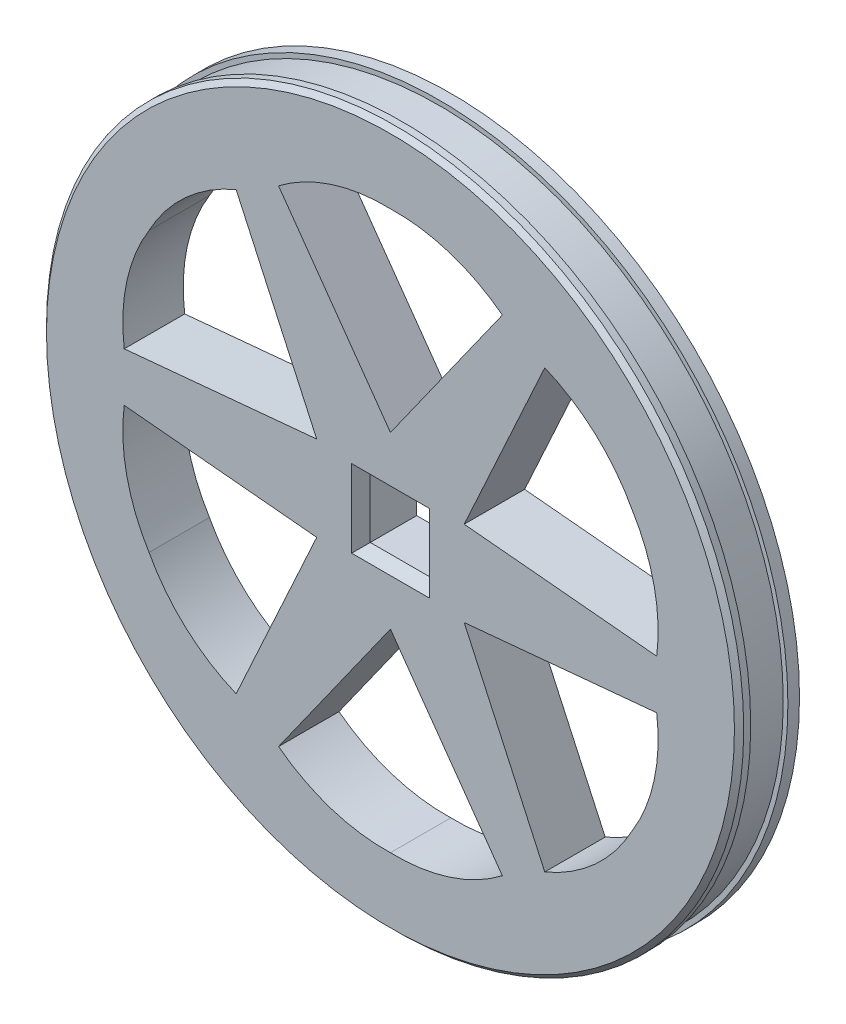
SolidWorks part; units mm, degrees
ref_plane "Front Plane" through (0, 0, 0) normal (0, 0, 1) x (1, 0, 0)
ref_plane "Top Plane" through (0, 0, 0) normal (0, 1, 0) x (1, 0, 0)
ref_plane "Right Plane" through (0, 0, 0) normal (1, 0, 0) x (0, 0, -1)
sketch "Sketch1" plane through (0, 0, 0) normal (0, 0, 1) x (1, 0, 0)
  line L1 (3.675, -3.675) -> (-3.675, -3.675)
  line L2 (3.675, -3.675) -> (3.675, 3.675)
  line L3 (3.675, 3.675) -> (-3.675, 3.675)
  line L4 (-3.675, -3.675) -> (-3.675, 3.675)
  circle A0 centre (0, 0) radius 37.5
  point P3 (0, 3.675)
  point P8 (0, 0)
  point P9 (3.675, 0)
  dimension "D1" = 75
  dimension "D2" = 7.35
  dimension "D3" = 7.35
extrude "Boss-Extrude1" add sketch "Sketch1" along normal mid plane 6.5
sketch "Sketch2" plane through (0, 0, 0) normal (0, 0, 1) x (1, 0, 0)
  line L0 (0, 0) -> (0, 32.5712) construction
  line L1 (0, 9.1586) -> (-12.0371, 26.1152)
  line L2 (0, 9.1586) -> (12.0371, 26.1152)
  arc A0 (-12.0371, 26.1152) -> (0, 29.9881) centre (-0.5568, 11.0765) cw
  arc A1 (12.0371, 26.1152) -> (0, 29.9881) centre (0.5568, 11.0765) ccw
extrude "Cut-Extrude1" cut sketch "Sketch2" along normal mid plane 8
pattern_circular "CirPattern1" count 6 over 360 about axis through (0, 0, 0) along (0, 0, 1) of "Cut-Extrude1"
sketch "Sketch3" plane through (0, 0, 0) normal (0, 0, 1) x (1, 0, 0)
  circle A0 centre (0, 0) radius 37.5
  circle A1 centre (0, 0) radius 37
  circle A2 centre (0, 0) radius 37.5 construction
  dimension "D1" = 0.5
extrude "Cut-Extrude2" cut sketch "Sketch3" against normal mid plane 4
chamfer "Chamfer1" distance 0.5 distance2 1.5 4 edges at (3.675, 0, 3.25) (0, 3.675, 3.25) (-3.675, 0, 3.25) (0, -3.675, 3.25)
chamfer "Chamfer2" distance 0.5 angle 45 1 edges at (37.5, 0, 3.25)
